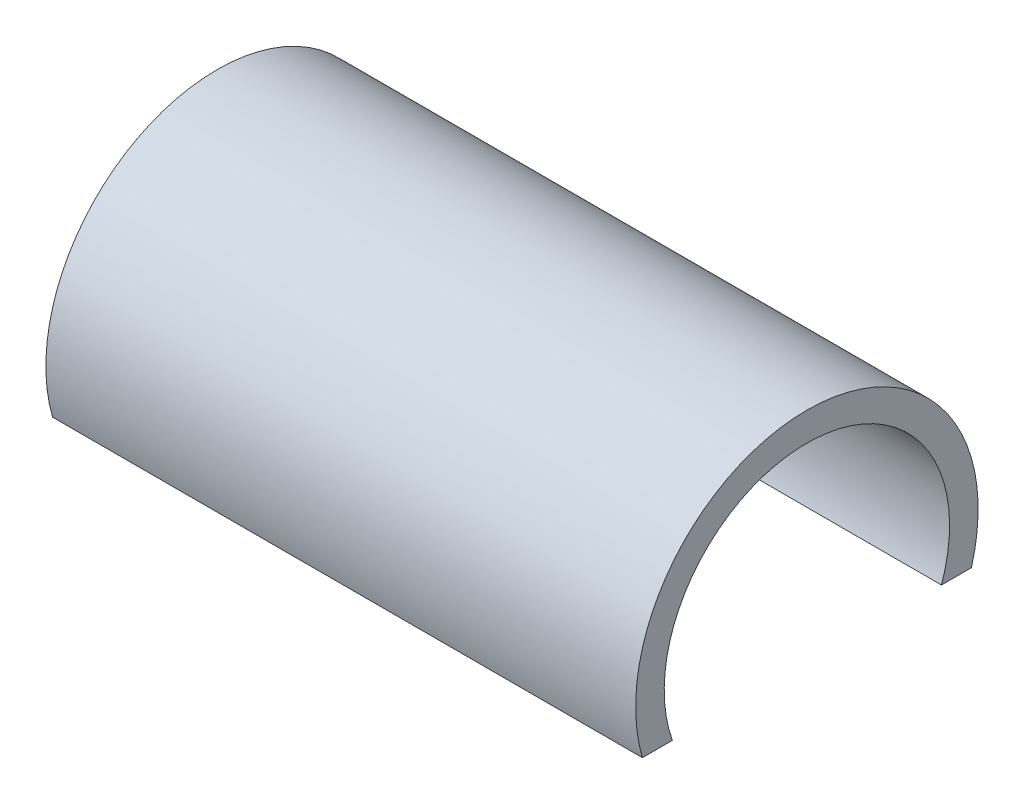
SolidWorks part; units mm, degrees
ref_plane "Plano frontal" through (0, 0, 0) normal (0, 0, 1) x (1, 0, 0)
ref_plane "Plano superior" through (0, 0, 0) normal (0, 1, 0) x (1, 0, 0)
ref_plane "Plano direito" through (0, 0, 0) normal (1, 0, 0) x (0, 0, -1)
sketch "Esboço1" plane through (0, 0, 0) normal (0, 0, 1) x (1, 0, 0)
  line L1 (27, -15) -> (-27, -15) construction
  line L2 (27, -15) -> (27, 15) construction
  line L3 (27, 15) -> (-27, 15) construction
  line L4 (-27, -15) -> (-27, 15) construction
  line L5 (27, -15) -> (-27, 15) construction
  line L6 (27, 15) -> (-27, -15) construction
  point P0 (0, 0)
  dimension "D1" = 30
  dimension "D2" = 54
ref_plane "Plano1" through (35, 0, 0) normal (1, 0, 0) x (0, 0, -1)
sketch "Esboço2" plane through (35, 0, 0) normal (1, 0, 0) x (0, 0, -1)
  circle A0 centre (0, 0) radius 15
  dimension "D1" = 30
extrude "Ressalto-extrusão1" add sketch "Esboço2" against normal blind 62
shell "Casca1" thickness 3
sketch "Esboço3" plane through (35, 0, 0) normal (1, 0, 0) x (0, 0, -1)
  line L2 (-17.2933, -4.9941) -> (17.2933, -4.9941)
  line L3 (0, 15) -> (0, 18) construction
  arc A0 (-17.2933, -4.9941) -> (17.2933, -4.9941) centre (0, 0) ccw
  circle A3 centre (0, 0) radius 18 construction
  point P7 (0, -4.9941)
  point P8 (0, 15.0059)
  dimension "D1" = 20
extrude "Corte-extrusão2" cut sketch "Esboço3" against normal through all
ref_plane "Plano2" through (0, 0, 35) normal (0, 0, 1) x (1, 0, 0)
sketch "Esboço5" plane through (0, 0, 35) normal (0, 0, 1) x (1, 0, 0)
  line L1 (-27, -4.9941) -> (35, -4.9941) construction
  line L3 (-27, -4.9941) -> (35, -4.9941)
  arc A0 (35, 15) -> (48.9363, 5.0029) centre (35.0169, 0.3112) cw
  point P4 (48.9363, 5.0029)
